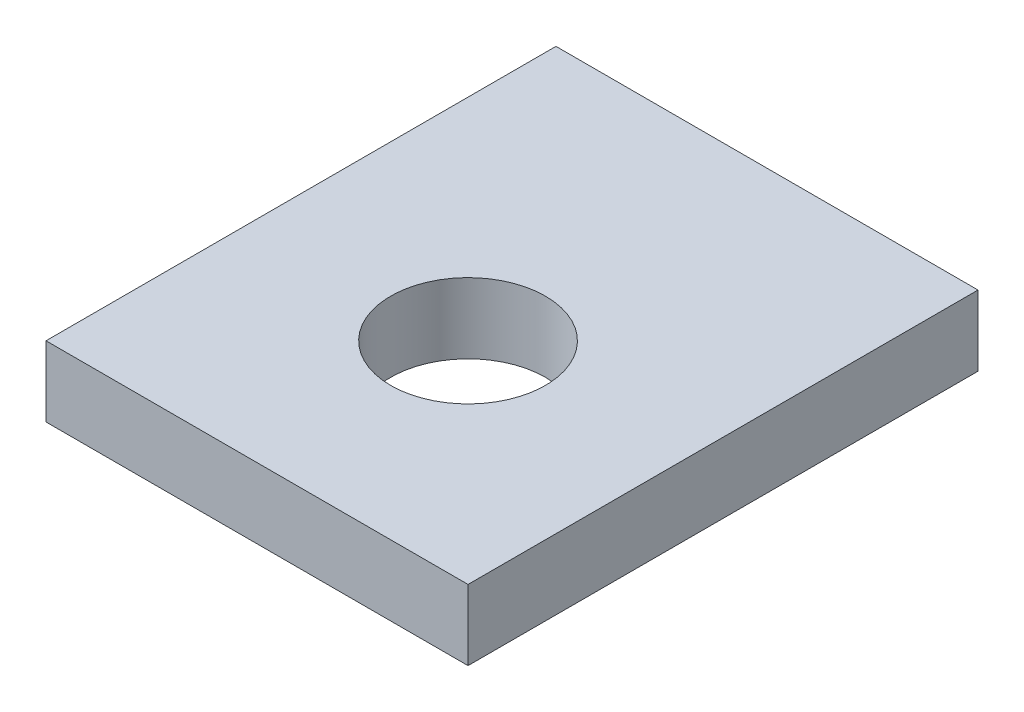
SolidWorks part; units mm, degrees
other "Encoder Board Edge Clamp 2"
ref_plane "Front Plane" through (0, 0, 0) normal (0, 0, 1) x (1, 0, 0)
ref_plane "Top Plane" through (0, 0, 0) normal (0, 1, 0) x (1, 0, 0)
ref_plane "Right Plane" through (0, 0, 0) normal (1, 0, 0) x (0, 0, -1)
sketch3d "Main Profile Sketch datum points"
  point P0 (0, -203.2, 0)
  point P1 (10, -203.2, 0)
  point P2 (0, -203.2, 10)
ref_plane "Main Profile Sketch plane" through (0, -203.2, 0) normal (0, -1, 0) x (-1, 0, 0)
sketch "Main Profile Sketch" plane through (0, -203.2, 0) normal (0, -1, 0) x (-1, 0, 0)
  line L0 (16.0092, 42.9949) -> (22.0092, 42.9949)
  line L1 (16.0092, 42.9949) -> (16.0092, 35.7449)
  line L2 (16.0092, 35.7449) -> (22.0092, 35.7449)
  line L3 (22.0092, 42.9949) -> (22.0092, 35.7449)
  circle A0 centre (19.0092, 38.7449) radius 1.1
extrude "Main Extrusion" add sketch "Main Profile Sketch" along normal blind 1 separate body
